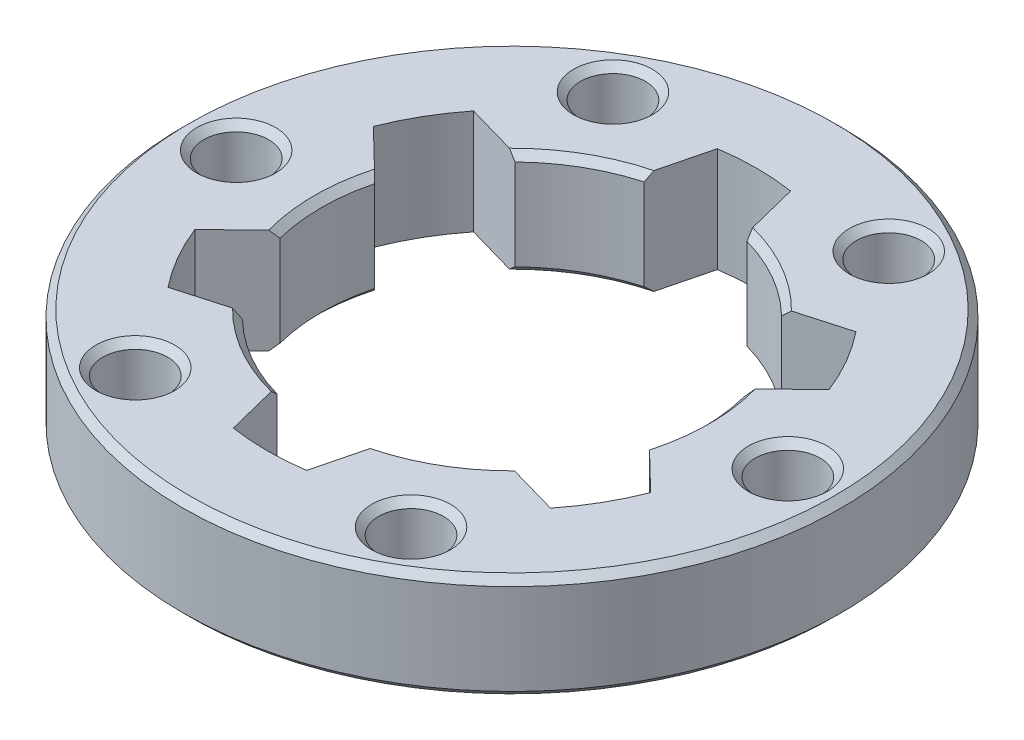
SolidWorks part; units mm, degrees
ref_plane "Plano frontal" through (0, 0, 0) normal (0, 0, 1) x (1, 0, 0)
ref_plane "Plano superior" through (0, 0, 0) normal (0, 1, 0) x (1, 0, 0)
ref_plane "Plano direito" through (0, 0, 0) normal (1, 0, 0) x (0, 0, -1)
sketch "Esboço1" plane through (0, 0, 0) normal (0, 0, 1) x (1, 0, 0)
  line L0 (0, -49.9228) -> (0, 53.4887) construction
  line L2 (27.3, 0) -> (47.2, 0)
  line L3 (27.3, 0) -> (27.3, 15)
  line L4 (27.3, 15) -> (47.2, 15)
  line L5 (47.2, 0) -> (47.2, 15)
  dimension "D1" = 27.3
  dimension "D2" = 47.2
  dimension "D3" = 15
revolve "Revolução1" add sketch "Esboço1" angle 360 about L0
sketch "Esboço2" plane through (0, 15, 0) normal (0, 1, 0) x (1, 0, 0)
  line L0 (-39.5, 0) -> (0, 0) construction
  circle A1 centre (0, 0) radius 39.5 construction
  circle A2 centre (-39.5, 0) radius 4.65
  circle A3 centre (-19.75, 34.208) radius 4.65
  circle A4 centre (19.75, 34.208) radius 4.65
  circle A5 centre (39.5, 0) radius 4.65
  circle A6 centre (19.75, -34.208) radius 4.65
  circle A7 centre (-19.75, -34.208) radius 4.65
  dimension "D1" = 79
  dimension "D2" = 9.3
  dimension "D3" = 6
extrude "Corte-extrusão1" cut sketch "Esboço2" against normal through all
sketch "Esboço3" plane through (0, 15, 0) normal (0, 1, 0) x (1, 0, 0)
  line L0 (0, 0) -> (0, 27.3) construction
  line L1 (5.25, 34.6546) -> (7.355, 26.2906)
  line L2 (32.6367, 12.7807) -> (26.4458, 6.7757)
  line L3 (-5.25, 34.6546) -> (-7.355, 26.2906)
  line L4 (27.3867, 21.8739) -> (19.0908, 19.5149)
  line L5 (27.3867, -21.8739) -> (19.0908, -19.5149)
  line L6 (32.6367, -12.7807) -> (26.4458, -6.7757)
  line L7 (-5.25, -34.6546) -> (-7.355, -26.2906)
  line L8 (5.25, -34.6546) -> (7.355, -26.2906)
  line L9 (-32.6367, -12.7807) -> (-26.4458, -6.7757)
  line L10 (-27.3867, -21.8739) -> (-19.0908, -19.5149)
  line L11 (-27.3867, 21.8739) -> (-19.0908, 19.5149)
  line L12 (-32.6367, 12.7807) -> (-26.4458, 6.7757)
  arc A0 (19.0908, 19.5149) -> (26.4458, 6.7757) centre (0, 0) cw
  circle A1 centre (0, 0) radius 27.3 construction
  arc A2 (-7.355, 26.2906) -> (7.355, 26.2906) centre (0, 0) cw
  arc A3 (-5.25, 34.6546) -> (5.25, 34.6546) centre (0, 0) cw
  arc A4 (27.3867, 21.8739) -> (32.6367, 12.7807) centre (0, 0) cw
  arc A5 (26.4458, -6.7757) -> (19.0908, -19.5149) centre (0, 0) cw
  arc A6 (32.6367, -12.7807) -> (27.3867, -21.8739) centre (0, 0) cw
  arc A7 (7.355, -26.2906) -> (-7.355, -26.2906) centre (0, 0) cw
  arc A8 (5.25, -34.6546) -> (-5.25, -34.6546) centre (0, 0) cw
  arc A9 (-19.0908, -19.5149) -> (-26.4458, -6.7757) centre (0, 0) cw
  arc A10 (-27.3867, -21.8739) -> (-32.6367, -12.7807) centre (0, 0) cw
  arc A11 (-26.4458, 6.7757) -> (-19.0908, 19.5149) centre (0, 0) cw
  arc A12 (-32.6367, 12.7807) -> (-27.3867, 21.8739) centre (0, 0) cw
  dimension "D1" = 6
extrude "Corte-extrusão2" cut sketch "Esboço3" against normal through all
chamfer "Chanfro1" distance 1 angle 45 10 edges at (-13.65, 15, 23.6425) (13.65, 15, 23.6425) (27.3, 15, 0) (-27.3, 0, 0) (-27.3, 15, 0) (13.65, 15, -23.6425) (-13.65, 0, -23.6425) (-13.65, 15, -23.6425) (0, 0, -47.2) (0, 15, -47.2)
chamfer "Chanfro2" distance 1 angle 45 4 edges at (-13.65, 0, 23.6425) (13.65, 0, 23.6425) (27.3, 0, 0) (13.65, 0, -23.6425)
chamfer "Chanfro3" distance 1 angle 45 6 edges at (19.75, 0, 38.858) (-19.75, 0, 38.858) (-39.5, 0, 4.65) (-19.75, 0, -29.558) (19.75, 0, -29.558) (39.5, 0, 4.65)
chamfer "Chanfro4" distance 1 angle 45 6 edges at (39.5, 15, 4.65) (19.75, 15, 38.858) (-19.75, 15, 38.858) (-39.5, 15, 4.65) (-19.75, 15, -29.558) (19.75, 15, -29.558)
